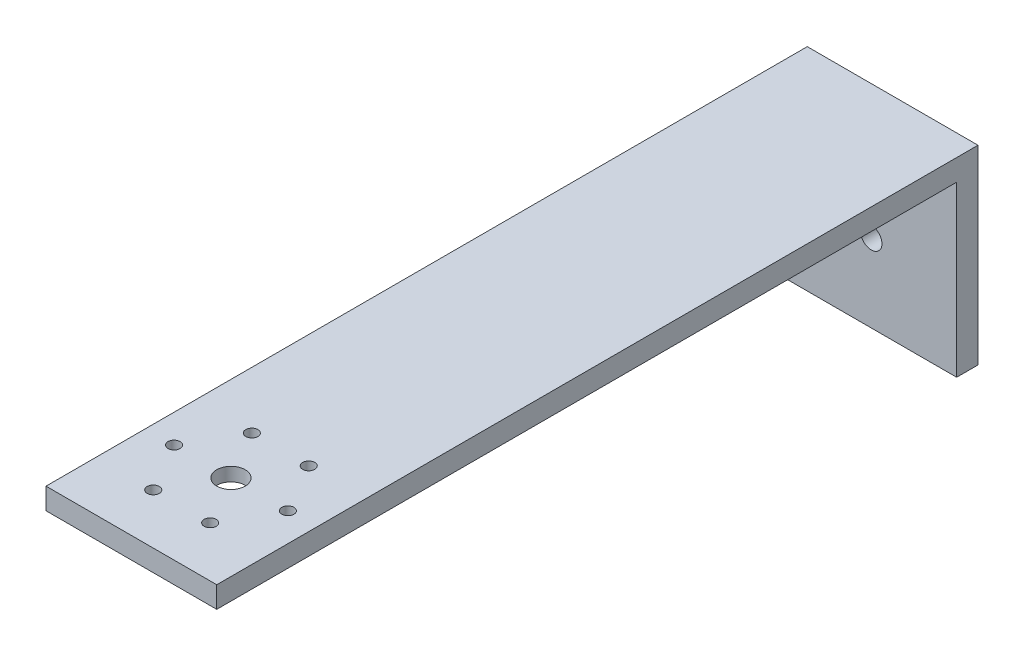
SolidWorks part; units mm, degrees
ref_plane "Front Plane" through (0, 0, 0) normal (0, 0, 1) x (1, 0, 0)
ref_plane "Top Plane" through (0, 0, 0) normal (0, 1, 0) x (1, 0, 0)
ref_plane "Right Plane" through (0, 0, 0) normal (1, 0, 0) x (0, 0, -1)
ref_plane "PL_Forearm_Plate_base" through (0, 25.5, 0) normal (0, 1, 0) x (1, 0, 0)
sketch "SK_Forearm_Plate" plane through (0, 25.5, 0) normal (0, 1, 0) x (1, 0, 0)
  line L0 (-24, -28) -> (24, -28)
  line L1 (24, -28) -> (24, 180)
  line L2 (24, 180) -> (-24, 180)
  line L3 (-24, 180) -> (-24, -28)
  circle A0 centre (16, 0) radius 1.7
  circle A1 centre (8, 13.8564) radius 1.7
  circle A2 centre (-8, 13.8564) radius 1.7
  circle A3 centre (-16, 0) radius 1.7
  circle A4 centre (-8, -13.8564) radius 1.7
  circle A5 centre (8, -13.8564) radius 1.7
  circle A6 centre (0, 0) radius 4
  dimension "D9_SK_Forearm_Plate" = 3.4
  dimension "D11_SK_Forearm_Plate" = 3.4
  dimension "D14_SK_Forearm_Plate" = 3.4
  dimension "D17_SK_Forearm_Plate" = 3.4
  dimension "D19_SK_Forearm_Plate" = 3.4
  dimension "D22_SK_Forearm_Plate" = 3.4
  dimension "D25_SK_Forearm_Plate" = 8
  dimension "P1" = 24
  dimension "P2" = 28
  dimension "P3" = 24
  dimension "P4" = 28
  dimension "P5" = 24
  dimension "P6" = 180
  dimension "P7" = 24
  dimension "P8" = 180
  dimension "P10" = 16
  dimension "P12" = 8
  dimension "P13" = 13.8564
  dimension "P15" = 8
  dimension "P16" = 13.8564
  dimension "P18" = 16
  dimension "P20" = 8
  dimension "P21" = 13.8564
  dimension "P23" = 8
  dimension "P24" = 13.8564
extrude "Forearm_Plate" add sketch "SK_Forearm_Plate" along normal blind 6
ref_plane "PL_Elbow_Pilot_Recess_base" through (0, 25.5, 0) normal (0, 1, 0) x (1, 0, 0)
sketch "SK_Elbow_Pilot_Recess" plane through (0, 25.5, 0) normal (0, 1, 0) x (1, 0, 0)
  circle A0 centre (0, 0) radius 12.15
  dimension "D1_SK_Elbow_Pilot_Recess" = 24.3
extrude "Elbow_Pilot_Recess" cut sketch "SK_Elbow_Pilot_Recess" along normal blind 2.2
ref_plane "PL_Hand_Plate_base" through (0, 0, -186) normal (0, 0, 1) x (1, 0, 0)
sketch "SK_Hand_Plate" plane through (0, 0, -186) normal (0, 0, 1) x (1, 0, 0)
  line L0 (-24, -22) -> (24, -22)
  line L1 (24, -22) -> (24, 31.5)
  line L2 (24, 31.5) -> (-24, 31.5)
  line L3 (-24, 31.5) -> (-24, -22)
  circle A0 centre (0, 0) radius 3
  dimension "D9_SK_Hand_Plate" = 6
  dimension "P1" = 24
  dimension "P2" = 22
  dimension "P3" = 24
  dimension "P4" = 22
  dimension "P5" = 24
  dimension "P6" = 31.5
  dimension "P7" = 24
  dimension "P8" = 31.5
extrude "Hand_Plate" add sketch "SK_Hand_Plate" along normal blind 6
equation "\"Forearm_length\" = 180"
